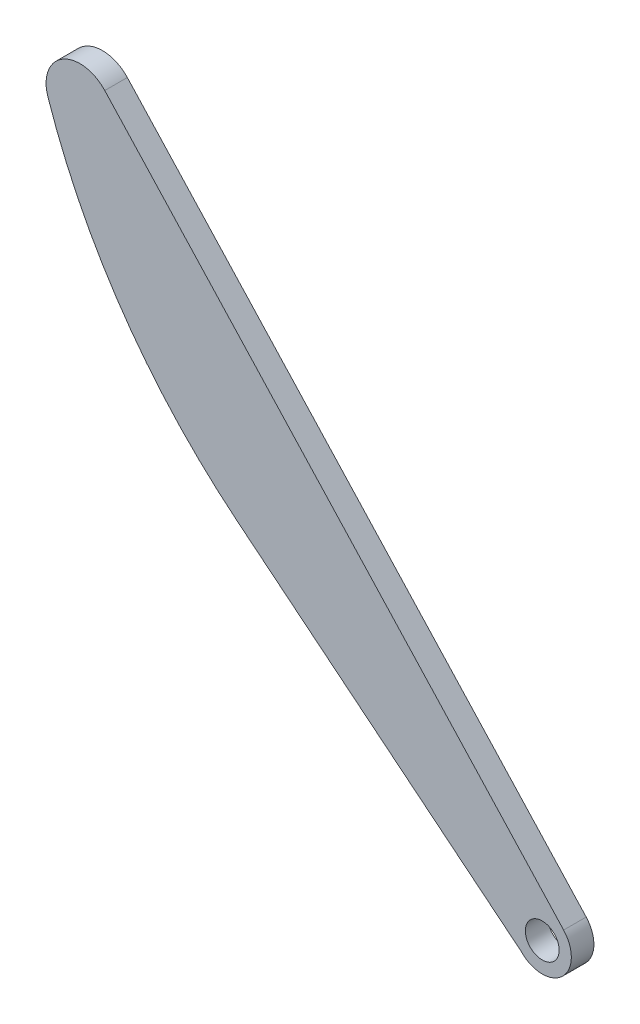
SolidWorks part; units mm, degrees
ref_plane "Front Plane" through (0, 0, 0) normal (0, 0, 1) x (1, 0, 0)
ref_plane "Top Plane" through (0, 0, 0) normal (0, 1, 0) x (1, 0, 0)
ref_plane "Right Plane" through (0, 0, 0) normal (1, 0, 0) x (0, 0, -1)
sketch "Sketch1" plane through (0, 0, 0) normal (0, 0, 1) x (1, 0, 0)
  line L0 (-46.6365, 42.789) -> (-50.061, 46.5028)
  line L1 (-50.061, 46.5028) -> (-86.5229, 86.045)
  line L2 (-86.5229, 86.045) -> (-94.8379, 95.0625)
  line L3 (-50.4299, 39.2911) -> (-75.5667, 59.7125)
  arc A0 (-75.5667, 59.7125) -> (-94.8379, 95.0625) centre (-42.132, 100.8674) cw
  arc A1 (-50.4299, 39.2911) -> (-46.6365, 42.789) centre (-48.5332, 41.0401) ccw
  circle A2 centre (-48.5332, 41.0401) radius 1.5
  dimension "D1" = 3
extrude "Boss-Extrude1" add sketch "Sketch1" along normal blind 2
fillet "Fillet1" radius 3 1 edges at (-94.8379, 95.0625, 1)
